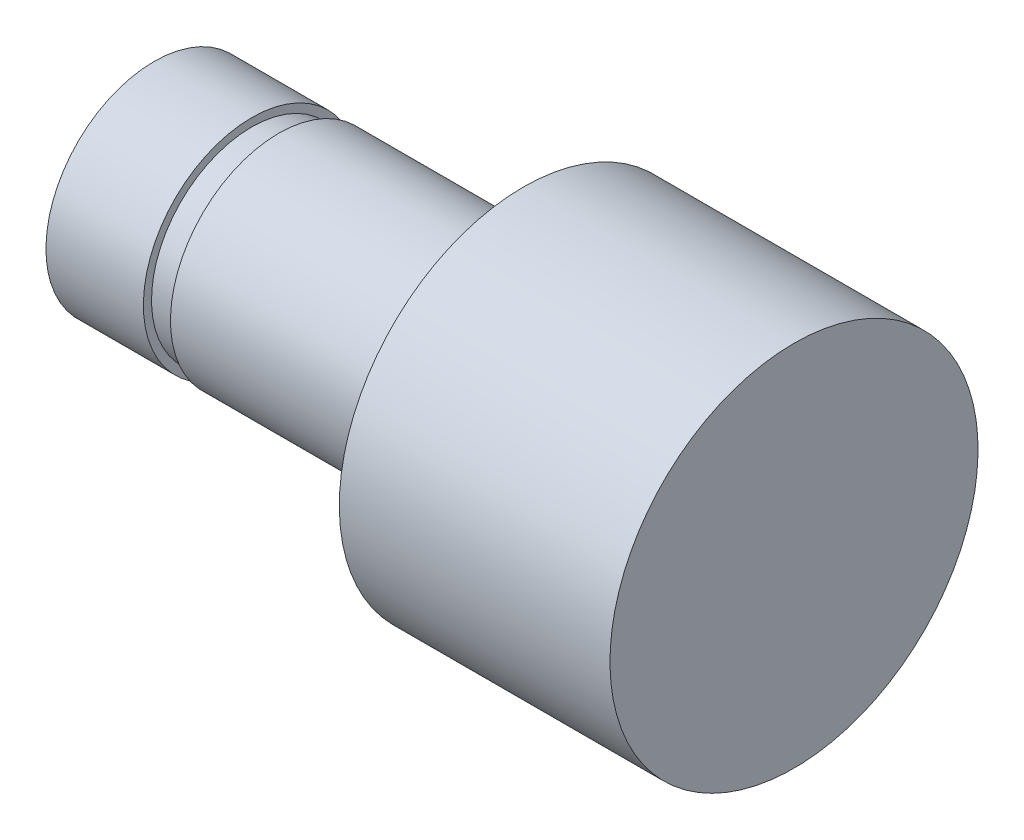
SolidWorks part; units mm, degrees
ref_plane "Vorne" through (0, 0, 0) normal (0, 0, 1) x (1, 0, 0)
ref_plane "Oben" through (0, 0, 0) normal (0, 1, 0) x (1, 0, 0)
ref_plane "Seite" through (0, 0, 0) normal (1, 0, 0) x (0, 0, -1)
sketch "Skizze2" plane through (0, 0, 0) normal (0, 0, 1) x (1, 0, 0)
  line L0 (2.6565, 0) -> (-9.1635, 0)
  line L1 (-9.1635, 0) -> (-9.1635, 2)
  line L2 (-9.1635, 2) -> (-7.3635, 2)
  line L3 (-7.3635, 2) -> (-7.3635, 1.85)
  line L4 (-7.3635, 1.85) -> (-6.8635, 1.85)
  line L5 (-6.8635, 1.85) -> (-6.8635, 2)
  line L6 (-6.8635, 2) -> (-2.3435, 2)
  line L7 (-2.3435, 2) -> (-2.3435, 3.4)
  line L8 (-2.3435, 3.4) -> (2.6565, 3.4)
  line L9 (2.6565, 3.4) -> (2.6565, 0)
  dimension "D1" = 0.5
  dimension "D2" = 0.15
  dimension "D3" = 1.8
  dimension "D4" = 4.52
  dimension "D5" = 5
  dimension "D6" = 3.4
  dimension "D7" = 2
revolve "Rotation1" add sketch "Skizze2" angle 360 about L0
